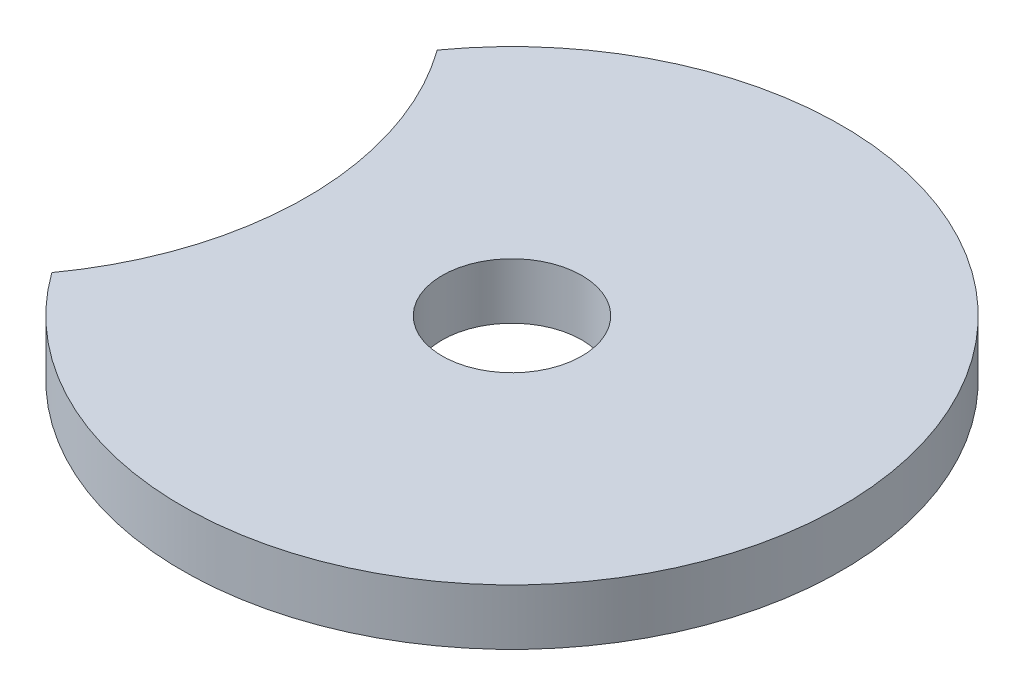
SolidWorks part; units mm, degrees
ref_plane "Front Plane" through (0, 0, 0) normal (0, 0, 1) x (1, 0, 0)
ref_plane "Top Plane" through (0, 0, 0) normal (0, 1, 0) x (1, 0, 0)
ref_plane "Right Plane" through (0, 0, 0) normal (1, 0, 0) x (0, 0, -1)
sketch "Sketch1" plane through (0, 0, 0) normal (0, 1, 0) x (1, 0, 0)
  line L0 (0, 0) -> (-72.9557, 0) construction
  arc A0 (-36.4778, -26.279) -> (-36.4778, 26.279) centre (0, 0) ccw
  circle A1 centre (0, 0) radius 9.525
  arc A2 (-36.4778, 26.279) -> (-36.4778, -26.279) centre (-72.9557, 0) cw
  dimension "D1" = 89.916
  dimension "D2" = 19.05
  dimension "D3" = 44.958
  dimension "D4" = 56.134
extrude "Boss-Extrude1" add sketch "Sketch1" along normal blind 7.62
